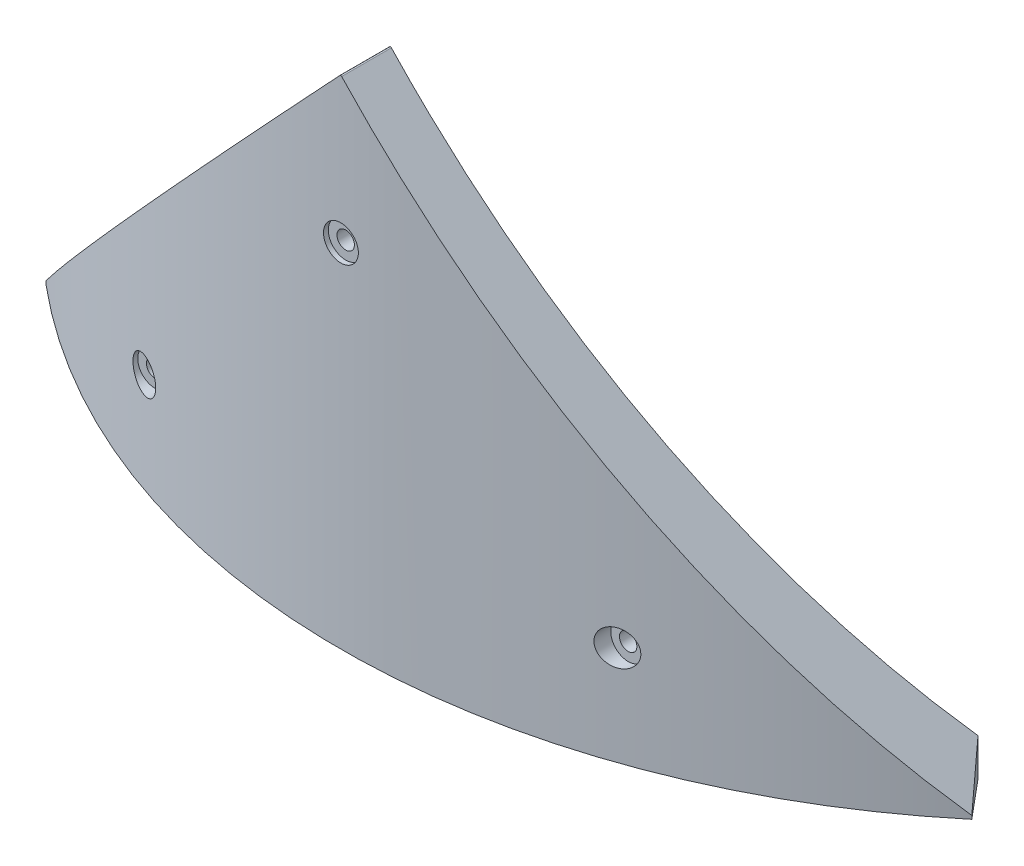
SolidWorks part; units mm, degrees
ref_plane "Front Plane" through (0, 0, 0) normal (0, 0, 1) x (1, 0, 0)
ref_plane "Top Plane" through (0, 0, 0) normal (0, 1, 0) x (1, 0, 0)
ref_plane "Right Plane" through (0, 0, 0) normal (1, 0, 0) x (0, 0, -1)
sketch "Sketch1" plane through (0, 0, 0) normal (0, 0, 1) x (1, 0, 0)
  line L0 (0, 65.7756) -> (0, -51.8654) construction
  line L1 (-93.7, 0) -> (93.7, 0)
  line L2 (-93.7, 0) -> (0, 100)
  line L3 (93.7, 0) -> (0, 100)
  point P7 (0, 0)
  dimension "D1" = 93.7
  dimension "D2" = 100
extrude "Boss-Extrude1" add sketch "Sketch1" along normal blind 100
sketch "Sketch3" plane through (0, 0, 0) normal (0, 1, 0) x (1, 0, 0)
  line L0 (-93.7, -50) -> (93.7, -50)
  line L1 (-93.7, -100) -> (-93.7, 0) construction
  line L2 (93.7, -100) -> (93.7, 0) construction
  line L3 (86.6499, -18.5219) -> (93.7, -26.9448)
  line L4 (-86.6499, -18.5219) -> (-93.7, -26.9448)
  line L7 (0, 85) -> (0, -142.8519) construction
  line L8 (93.7, -26.9448) -> (117.2862, 18.1498)
  line L9 (-93.7, -26.9448) -> (-117.2862, 18.1498)
  arc A0 (117.2862, 18.1498) -> (-117.2862, 18.1498) centre (0, 85) ccw
  arc A1 (-86.6499, -18.5219) -> (86.6499, -18.5219) centre (0, 85) ccw
  dimension "D1" = 270
  dimension "D2" = 79.86
extrude "Cut-Extrude1" cut sketch "Sketch3" along normal blind 100 contours A0
sketch "Sketch4" plane through (0, 0, 0) normal (0, 1, 0) x (1, 0, 0)
  line L0 (-145, 85) -> (-145, -157.2708)
  line L1 (-145, -157.2708) -> (195.8377, -157.2708)
  line L2 (195.8377, -157.2708) -> (144.5177, 73.1834)
  arc A4 (-145, 85) -> (144.5177, 73.1834) centre (0, 85) ccw
extrude "Cut-Extrude3" cut sketch "Sketch4" along normal blind 100
fillet "Fillet1" radius 0.25 1 edges at (0, 100, 55)
sketch "Sketch5" plane through (0, 0, 0) normal (0, 0, 1) x (1, 0, 0)
  line L12 (-47.5522, 20) -> (47.5522, 20)
  line L13 (0, 70.7494) -> (-47.5522, 20)
  line L14 (47.5522, 20) -> (0, 70.7494)
  circle A0 centre (47.5522, 20) radius 1.75
  circle A1 centre (0, 70.7494) radius 1.75
  circle A2 centre (-47.5522, 20) radius 1.75
  dimension "D2" = 3.5
  dimension "D3" = 3.5
  dimension "D4" = 3.5
extrude "Cut-Extrude4" cut sketch "Sketch5" along normal blind 100 contours L14 A1 L13 | L13 A1 L14 | L12 A0 L14 | L14 A0 L12 | L13 A2 L12 | L12 A2 L13
ref_plane "Plane1" through (0, 0, 60) normal (0, 0, 1) x (1, 0, 0)
sketch "Sketch6" plane through (0, 0, 60) normal (0, 0, 1) x (1, 0, 0)
  circle A0 centre (0, 70.7494) radius 3.5
extrude "Cut-Extrude5" cut sketch "Sketch6" against normal blind 1
sketch "Sketch7" plane through (0, 0, 60) normal (0, 0, 1) x (1, 0, 0)
  circle A0 centre (-47.5522, 20) radius 3.5
  circle A1 centre (47.5522, 20) radius 3.5
extrude "Cut-Extrude6" cut sketch "Sketch7" against normal blind 10.24
